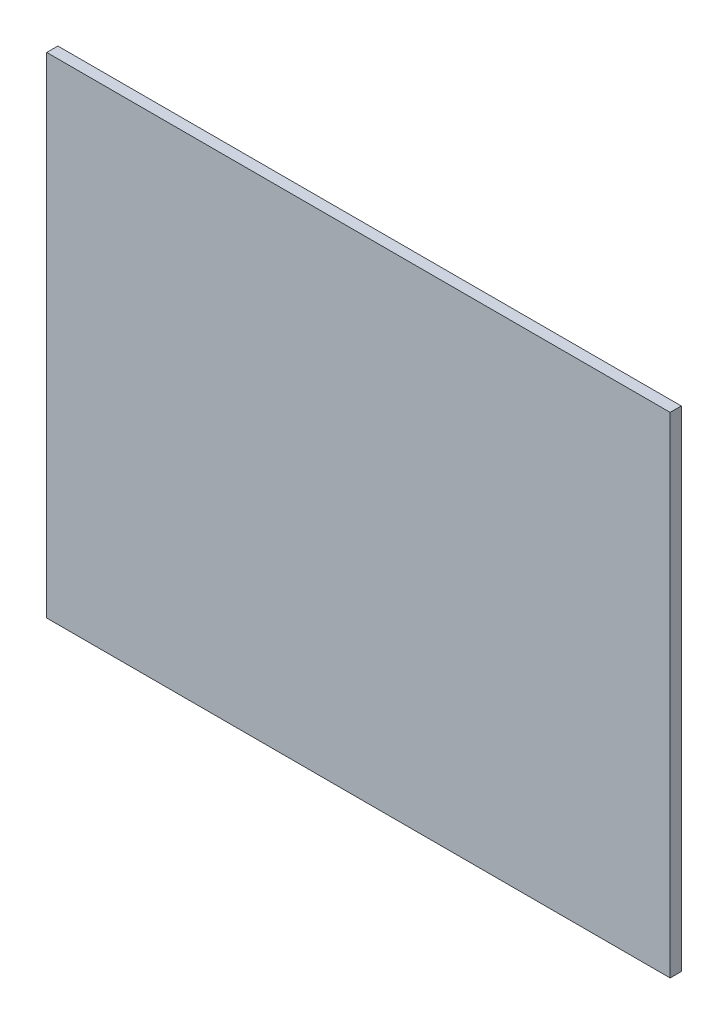
SolidWorks part; units mm, degrees
ref_plane "Front Plane" through (0, 0, 0) normal (0, 0, 1) x (1, 0, 0)
ref_plane "Top Plane" through (0, 0, 0) normal (0, 1, 0) x (1, 0, 0)
ref_plane "Right Plane" through (0, 0, 0) normal (1, 0, 0) x (0, 0, -1)
sketch "Sketch1" plane through (0, 0, 0) normal (0, 0, 1) x (1, 0, 0)
  line L1 (177.8, -139.7) -> (-177.8, -139.7)
  line L2 (177.8, -139.7) -> (177.8, 139.7)
  line L3 (177.8, 139.7) -> (-177.8, 139.7)
  line L4 (-177.8, -139.7) -> (-177.8, 139.7)
  line L5 (177.8, -139.7) -> (-177.8, 139.7) construction
  line L6 (177.8, 139.7) -> (-177.8, -139.7) construction
  point P0 (0, 0)
  dimension "D1" = 279.4
  dimension "D2" = 355.6
extrude "Boss-Extrude1" add sketch "Sketch1" along normal blind 6.35
